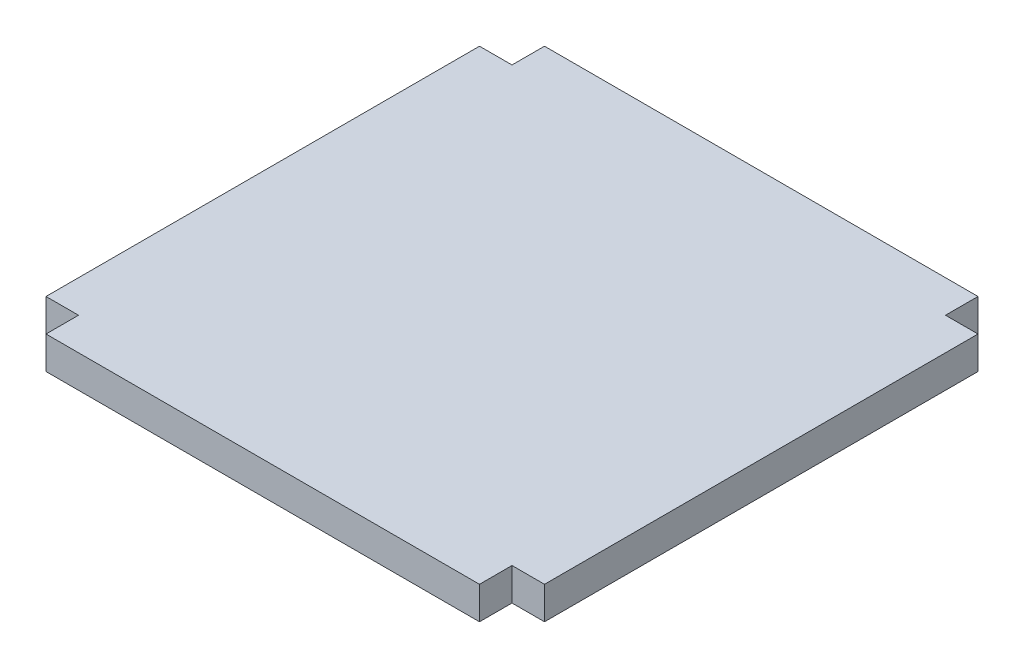
SolidWorks part; units mm, degrees
ref_plane "前视基准面" through (0, 0, 0) normal (0, 0, 1) x (1, 0, 0)
ref_plane "上视基准面" through (0, 0, 0) normal (0, 1, 0) x (1, 0, 0)
ref_plane "右视基准面" through (0, 0, 0) normal (1, 0, 0) x (0, 0, -1)
sketch "草图1" plane through (0, 0, 0) normal (0, 1, 0) x (1, 0, 0)
  line L0 (-115, 100) -> (-100, 100)
  line L1 (-100, 115) -> (100, 115)
  line L2 (-115, 100) -> (-115, -100)
  line L3 (-100, -115) -> (100, -115)
  line L4 (115, 100) -> (115, -100)
  line L5 (-100, 100) -> (100, -100) construction
  line L6 (-100, -100) -> (100, 100) construction
  line L7 (-100, 100) -> (-100, 115)
  line L8 (100, -100) -> (115, -100)
  line L9 (100, -115) -> (100, -100)
  line L10 (0, 106.6681) -> (0, -111.7087) construction
  line L11 (100, 100) -> (100, 115)
  line L12 (115, 100) -> (100, 100)
  line L13 (-100, -115) -> (-100, -100)
  line L14 (-100, -100) -> (-115, -100)
  point P0 (0, 0)
  dimension "D1" = 200
  dimension "D3" = 15
extrude "凸台-拉伸1" add sketch "草图1" along normal blind 15
